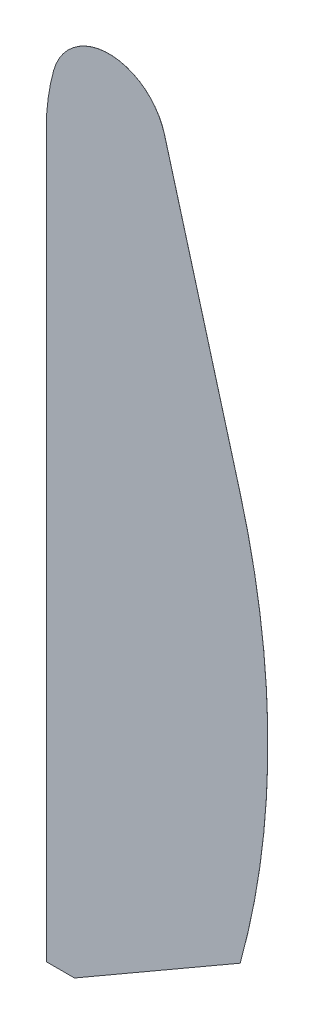
SolidWorks part; units mm, degrees
ref_plane "Front Plane" through (0, 0, 0) normal (1, 0, 0) x (0, 1, 0)
ref_plane "Top Plane" through (0, 0, 0) normal (0, 0, 1) x (0, 1, 0)
ref_plane "Right Plane" through (0, 0, 0) normal (0, 1, 0) x (-1, 0, 0)
sketch "Sketch1" plane through (0, 0, 0) normal (0, 0, 1) x (0, 1, 0)
  line L0 (0, 0) -> (0, 50000) construction
  line L1 (0, 0) -> (50000, 0) construction
  line L2 (143.5634, 601.065) -> (1381.2364, 932.6984) construction
  line L3 (0, 0) -> (127.875, 0)
  line L4 (0, 0) -> (0, -5)
  line L5 (0, -5) -> (16.9597, -34.375)
  line L6 (137.5, -20.953) -> (89.1119, -34.375)
  line L7 (0, 0) -> (53.0358, -39.2857)
  line L8 (0, 0) -> (137.5, -20.953)
  arc A0 (127.875, 0) -> (137.5, -1.3102) centre (127.875, -36.0097) cw
  arc A1 (137.5, -1.3102) -> (137.5, -20.953) centre (134.7757, -11.1316) cw
  arc A2 (16.9597, -34.375) -> (89.1119, -34.375) centre (53.0358, 95.6845) ccw
  dimension "D1" = 5
  dimension "D2" = 34.375
  dimension "D3" = 127.875
  dimension "Span" = 137.5
  dimension "Chord" = 39.2857
  dimension "D4" = 30
  dimension "D5" = 19.6429
extrude "Boss-Extrude1" add sketch "Sketch1" along normal blind 0.01 contours L6 A2 L5 L4 L3 A0 A1
equation "\"D3@Sketch1\"=\"Span@Sketch1\"*0.93"
equation "\"D2@Sketch1\"=\"Chord@Sketch1\"*0.875"
equation "\"Chord@Sketch1\"=\"Span@Sketch1\"/3.5"
equation "\"D5@Sketch1\"=\"Chord@Sketch1\"/2"
